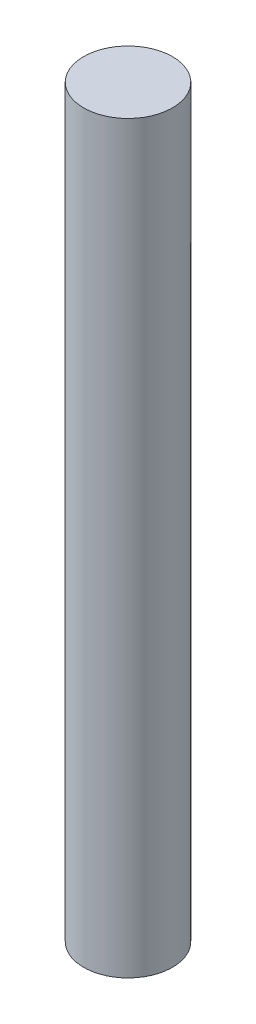
SolidWorks part; units mm, degrees
ref_plane "Front" through (0, 0, 0) normal (0, 0, 1) x (1, 0, 0)
ref_plane "Top" through (0, 0, 0) normal (0, 1, 0) x (1, 0, 0)
ref_plane "Right" through (0, 0, 0) normal (1, 0, 0) x (0, 0, -1)
sketch "Sketch1" plane through (0, 0, 0) normal (0, 0, 1) x (1, 0, 0)
  line L0 (-2, 15.4211) -> (2, 15.4211) construction
  line L1 (0, -26.4789) -> (2.5, -26.4789)
  line L2 (0, -26.4789) -> (0, 15.4211)
  line L3 (0, 15.4211) -> (2.5, 15.4211)
  line L4 (2.5, -26.4789) -> (2.5, 15.4211)
  line L5 (2, -26.4789) -> (-2, -26.4789) construction
  dimension "D1" = 2.5
revolve "Revolve1" add sketch "Sketch1" angle 360 about L2
